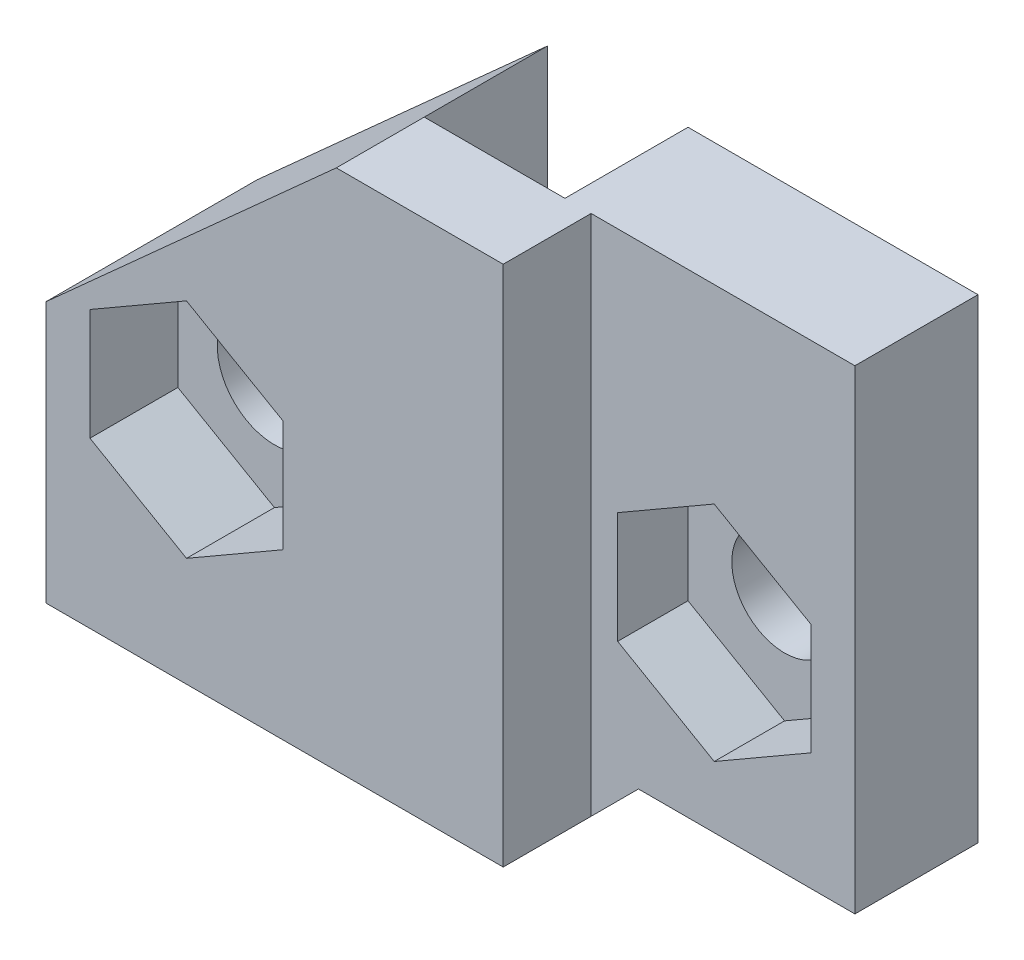
SolidWorks part; units mm, degrees
ref_plane "Alzado" through (0, 0, 0) normal (0, 0, 1) x (1, 0, 0)
ref_plane "Planta" through (0, 0, 0) normal (0, 1, 0) x (1, 0, 0)
ref_plane "Vista lateral" through (0, 0, 0) normal (1, 0, 0) x (0, 0, -1)
sketch "Croquis1" plane through (0, 0, 0) normal (0, 0, 1) x (1, 0, 0)
  line L0 (88.7324, -80.1486) -> (88.7324, -81.4936)
  line L1 (88.7324, -66.6486) -> (96.2324, -66.6486)
  line L2 (88.7324, -66.6486) -> (88.7324, -80.1486)
  line L3 (90.0774, -80.1486) -> (96.2324, -80.1486)
  line L4 (96.2324, -66.6486) -> (96.2324, -80.1486)
  line L5 (88.7324, -81.4936) -> (90.0774, -80.1486)
  circle A0 centre (92.2324, -75.2236) radius 1.5
  dimension "D1" = 3
extrude "Saliente-Extruir1" add sketch "Croquis1" along normal blind 3.5
sketch "Croquis2" plane through (0, 0, 3.5) normal (0, 0, 1) x (1, 0, 0)
  line L1 (92.2324, -72.0536) -> (89.4871, -73.6386)
  line L2 (89.4871, -73.6386) -> (89.4871, -76.8086)
  line L3 (89.4871, -76.8086) -> (92.2324, -78.3936)
  line L4 (92.2324, -78.3936) -> (94.9777, -76.8086)
  line L5 (94.9777, -76.8086) -> (94.9777, -73.6386)
  line L6 (94.9777, -73.6386) -> (92.2324, -72.0536)
  circle A0 centre (92.2324, -75.2236) radius 2.7453 construction
  dimension "D1" = 5.4906
extrude "Cortar-Extruir1" cut sketch "Croquis2" against normal blind 2
sketch "Croquis3" plane through (0, 0, 3.5) normal (0, 0, 1) x (1, 0, 0)
  line L0 (88.7324, -81.4936) -> (75.7324, -81.4936)
  line L1 (75.7324, -81.4936) -> (75.7324, -74.0711)
  line L2 (75.7324, -74.0711) -> (83.9871, -66.6486)
  line L3 (87.9871, -66.6486) -> (88.7324, -66.6486)
  line L4 (88.7324, -66.6486) -> (88.7324, -81.4936)
  line L5 (83.9871, -66.6486) -> (83.9871, -75.2236)
  line L6 (83.9871, -75.2236) -> (87.9871, -75.2236)
  line L7 (87.9871, -75.2236) -> (87.9871, -66.6486)
  line L8 (87.9871, 53.1061) -> (87.9871, -75.2236) construction
  circle A0 centre (79.7277, -75.2236) radius 1.625
  dimension "D1" = 3.25
extrude "Saliente-Extruir2" add sketch "Croquis3" against normal blind 3.5 and the other way blind 2.5
sketch "Croquis4" plane through (0, 0, 6) normal (0, 0, 1) x (1, 0, 0)
  line L1 (83.9871, -66.6486) -> (87.9871, -66.6486)
  line L2 (83.9871, -66.6486) -> (83.9871, -75.2236)
  line L3 (83.9871, -75.2236) -> (87.9871, -75.2236)
  line L4 (87.9871, -66.6486) -> (87.9871, -75.2236)
extrude "Saliente-Extruir3" add sketch "Croquis4" against normal blind 2.5
sketch "Croquis5" plane through (0, 0, 6) normal (0, 0, 1) x (1, 0, 0)
  line L1 (79.7277, -78.3936) -> (82.473, -76.8086)
  line L2 (82.473, -76.8086) -> (82.473, -73.6386)
  line L3 (82.473, -73.6386) -> (79.7277, -72.0536)
  line L4 (79.7277, -72.0536) -> (76.9824, -73.6386)
  line L5 (76.9824, -73.6386) -> (76.9824, -76.8086)
  line L6 (76.9824, -76.8086) -> (79.7277, -78.3936)
  circle A0 centre (79.7277, -75.2236) radius 2.7453 construction
  dimension "D1" = 5.4906
extrude "Cortar-Extruir2" cut sketch "Croquis5" against normal blind 2.5
